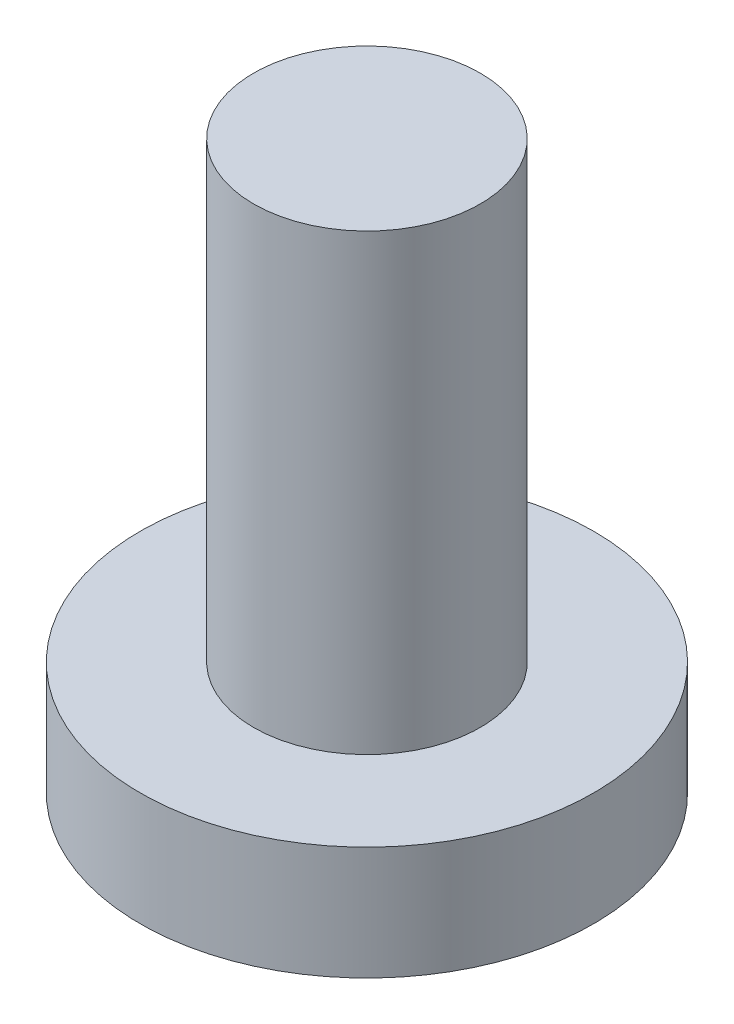
SolidWorks part; units mm, degrees
ref_plane "Front Plane" through (0, 0, 0) normal (0, 0, 1) x (1, 0, 0)
ref_plane "Top Plane" through (0, 0, 0) normal (0, 1, 0) x (1, 0, 0)
ref_plane "Right Plane" through (0, 0, 0) normal (1, 0, 0) x (0, 0, -1)
sketch "Sketch1" plane through (0, 0, 0) normal (0, 0, 1) x (1, 0, 0)
  line L0 (0, -3.3671) -> (0, 12.9367) construction
  line L1 (0, 0) -> (4, 0)
  line L2 (4, 0) -> (4, 2)
  line L3 (4, 2) -> (2, 2)
  line L4 (2, 2) -> (2, 10)
  line L5 (2, 10) -> (0, 10)
  line L6 (0, 10) -> (0, 0)
  line L7 (0, 0) -> (0.0506, -0.0253)
  dimension "D1" = 2
  dimension "D2" = 4
  dimension "D3" = 2
  dimension "D4" = 8
revolve "Revolve1" add sketch "Sketch1" angle 360 about L0
